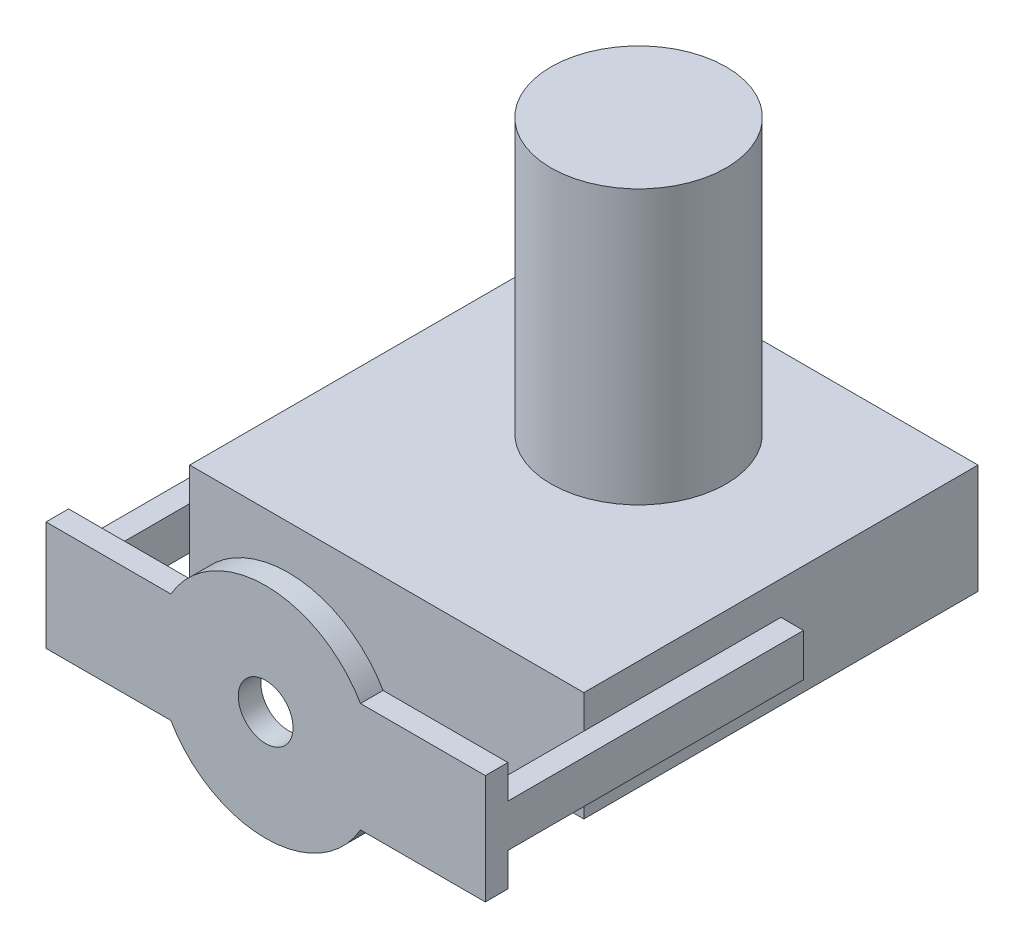
SolidWorks part; units mm, degrees
ref_plane "前视基准面" through (0, 0, 0) normal (0, 0, 1) x (1, 0, 0)
ref_plane "上视基准面" through (0, 0, 0) normal (0, 1, 0) x (1, 0, 0)
ref_plane "右视基准面" through (0, 0, 0) normal (1, 0, 0) x (0, 0, -1)
sketch "草图1" plane through (0, 0, 0) normal (0, 1, 0) x (1, 0, 0)
  line L1 (-18, 18) -> (18, 18)
  line L2 (-18, 18) -> (-18, -18)
  line L3 (-18, -18) -> (18, -18)
  line L4 (18, 18) -> (18, -18)
  line L5 (-18, 18) -> (18, -18) construction
  line L6 (-18, -18) -> (18, 18) construction
  point P0 (0, 0)
  dimension "D1" = 36
  dimension "D2" = 36
extrude "凸台-拉伸1" add sketch "草图1" along normal blind 10
sketch "草图3" plane through (0, 10, 0) normal (0, 1, 0) x (1, 0, 0)
  line L0 (0, 11.8921) -> (0, -6.4898) construction
  circle A0 centre (0, 5) radius 8
  point P2 (0, 0)
  dimension "D2" = 16
  dimension "D1" = 5
extrude "凸台-拉伸2" add sketch "草图3" along normal blind 25
sketch "草图4" plane through (-18, 0, 0) normal (-1, 0, 0) x (0, 0, 1)
  line L1 (0, 3.05) -> (27, 3.05)
  line L2 (0, 3.05) -> (0, 6.95)
  line L3 (0, 6.95) -> (27, 6.95)
  line L4 (27, 3.05) -> (27, 6.95)
  line L5 (0, 3.05) -> (27, 6.95) construction
  line L6 (0, 6.95) -> (27, 3.05) construction
  line L7 (14.633, 5) -> (25.9671, 5) construction
  line L9 (18, 10) -> (18, 0) construction
  point P0 (13.5, 5)
  point P5 (14.633, 6.1648)
  point P7 (0, 0)
  point P9 (18, 5)
  dimension "D1" = 3.9
  dimension "D2" = 9
  dimension "D3" = 18
extrude "凸台-拉伸3" add sketch "草图4" along normal blind 2.0631
sketch "草图5" plane through (18, 0, 0) normal (1, 0, 0) x (0, 0, -1)
  line L0 (-27, 3.05) -> (0, 3.05)
  line L1 (-27, 6.95) -> (0, 6.95)
  line L2 (0, 3.05) -> (0, 6.95)
  line L3 (-27, 3.05) -> (0, 6.95) construction
  line L4 (-27, 6.95) -> (0, 3.05) construction
  line L5 (-19.4048, 5) -> (0.7098, 5) construction
  line L6 (-27, 3.05) -> (-27, 6.95)
  line L7 (-18, 10) -> (-18, 0) construction
  point P6 (-19.4048, 2.9043)
  point P7 (-13.5, 5)
  point P10 (-18, 5)
  dimension "D1" = 3.9
  dimension "D2" = 9
  dimension "D3" = 18
extrude "凸台-拉伸4" add sketch "草图5" along normal blind 2.0631
sketch "草图6" plane through (0, 0, 27) normal (0, 0, 1) x (1, 0, 0)
  line L0 (0, -8.3525) -> (0, 18.3525) construction
  line L1 (22.8529, 5) -> (-22.8529, 5) construction
  line L2 (-20.0631, 3.05) -> (-20.0631, 6.95) construction
  line L3 (20.0631, 3.05) -> (20.0631, 0)
  line L4 (20.0631, 0) -> (8.6603, 0)
  line L5 (-20.0631, 0) -> (-20.0631, 10)
  line L6 (-20.0631, 10) -> (-8.6603, 10)
  line L7 (20.0631, 10) -> (20.0631, 3.05)
  line L8 (-8.6603, 0) -> (-20.0631, 0)
  line L9 (8.6603, 10) -> (20.0631, 10)
  arc A0 (-8.6603, 0) -> (8.6603, 0) centre (0, 5) ccw
  arc A1 (8.6603, 10) -> (-8.6603, 10) centre (0, 5) ccw
  circle A2 centre (0, 5) radius 2.5
  point P10 (-20.0631, 5)
  point P13 (-20.0631, 5)
  dimension "D1" = 20
  dimension "D2" = 5
extrude "凸台-拉伸5" add sketch "草图6" along normal blind 2.0631
